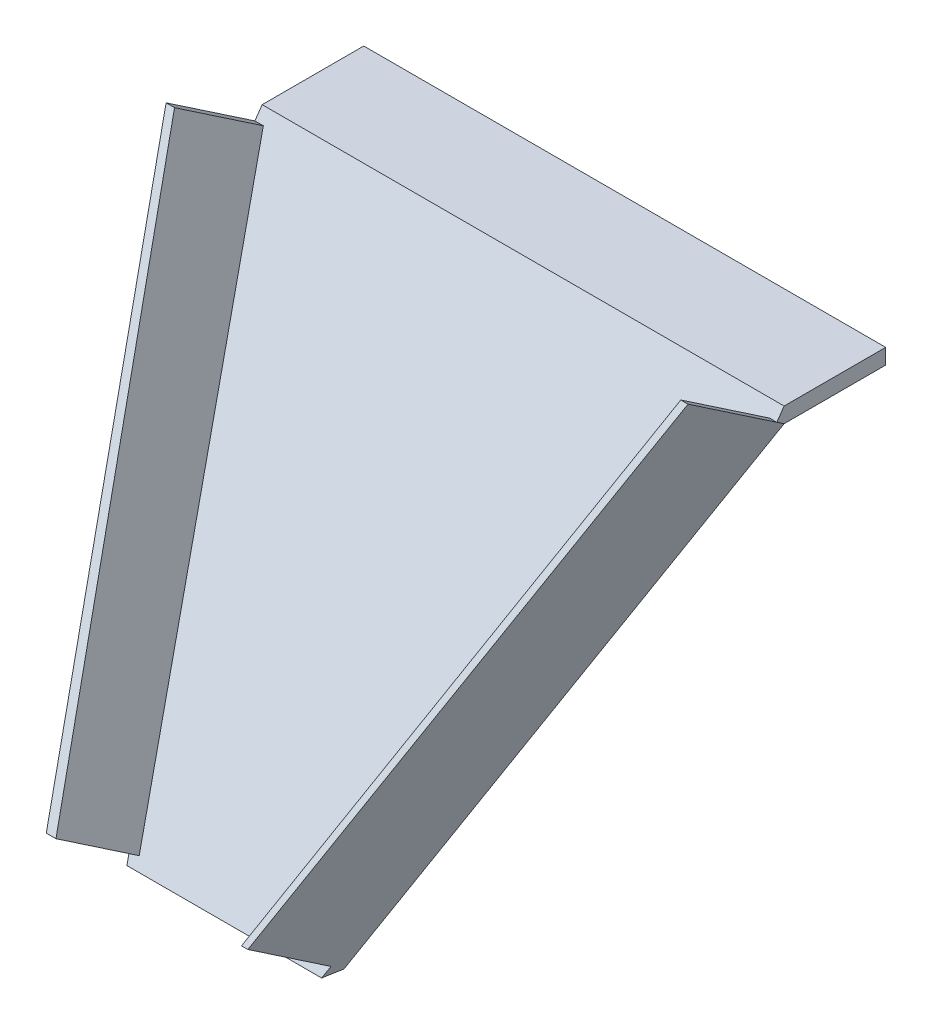
SolidWorks part; units mm, degrees
ref_plane "Front Plane" through (0, 0, 0) normal (0, 0, 1) x (1, 0, 0)
ref_plane "Top Plane" through (0, 0, 0) normal (0, 1, 0) x (1, 0, 0)
ref_plane "Right Plane" through (0, 0, 0) normal (1, 0, 0) x (0, 0, -1)
sketch "Sketch1" plane through (0, 0, 0) normal (1, 0, 0) x (0, 0, -1)
  line L0 (-25.7143, -36.9293) -> (25.7143, 36.9293)
  line L1 (25.7143, 36.9293) -> (43.2325, 36.9293)
  line L2 (43.2325, 36.9293) -> (43.2325, 34.282)
  line L3 (43.2325, 34.282) -> (25.7143, 34.282)
  line L4 (25.7143, 34.282) -> (-22.4606, -36.9293)
  line L5 (-22.4606, -36.9293) -> (-25.7143, -36.9293)
  point P4 (0, 0)
  point P5 (0, 0)
  point P7 (16.8772, 41.7152)
extrude "Boss-Extrude1" add sketch "Sketch1" along normal blind 90
sketch "Sketch5" plane through (0, -1.1706, -1.7304) normal (0, -0.5603, -0.8283) x (-1, 0, 0)
  line L0 (-90, 42.8032) -> (-61.6829, -44.9959)
  line L1 (-90, -44.9959) -> (0, -44.9959) construction
extrude "Cut-Extrude-Thin5" cut sketch "Sketch5" against normal blind 90 and the other way through all thin
sketch "Sketch6" plane through (0, -1.1706, -1.7304) normal (0, -0.5603, -0.8283) x (-1, 0, 0)
  line L0 (0, 42.8032) -> (-28.1023, -44.9959)
  line L1 (-61.6829, -44.9959) -> (0, -44.9959) construction
extrude "Cut-Extrude-Thin6" cut sketch "Sketch6" against normal blind 90 and the other way through all thin thin type one direction reverse wall 30
sketch "Sketch7" plane through (0, -1.1706, -1.7304) normal (0, -0.5603, -0.8283) x (-1, 0, 0)
  line L0 (-88.7527, 42.8032) -> (-61.1775, -43.1728)
  line L1 (-90, 42.8032) -> (0, 42.8032) construction
  line L2 (-62.2709, -43.1728) -> (-27.5188, -43.1728) construction
  line L7 (-27.5188, -43.1728) -> (0, 42.8032)
  line L8 (0, 42.8032) -> (-90, 42.8032)
  line L9 (-90, 42.8032) -> (-62.2709, -43.1728)
  line L10 (-62.2709, -43.1728) -> (-27.5188, -43.1728)
  line L12 (-88.7527, 42.8032) -> (-90, 42.8032)
  line L13 (-90, 42.8032) -> (-62.2709, -43.1728)
  line L14 (-62.2709, -43.1728) -> (-61.1775, -43.1728)
  dimension "D1" = 0
extrude "Boss-Extrude2" add sketch "Sketch7" against normal blind 20
sketch "Sketch8" plane through (0, -1.1706, -1.7304) normal (0, -0.5603, -0.8283) x (-1, 0, 0)
  line L0 (-1.4559, 42.8032) -> (-29.1844, -43.1728)
  line L1 (-90, 42.8032) -> (0, 42.8032) construction
  line L2 (-62.2709, -43.1728) -> (-27.5188, -43.1728) construction
  line L7 (-90, 42.8032) -> (-62.2709, -43.1728)
  line L8 (-62.2709, -43.1728) -> (-27.5188, -43.1728)
  line L9 (-27.5188, -43.1728) -> (0, 42.8032)
  line L10 (0, 42.8032) -> (-90, 42.8032)
  line L12 (-62.2709, -43.1728) -> (-29.1844, -43.1728)
  line L14 (-1.4559, 42.8032) -> (-90, 42.8032)
  line L15 (-90, 42.8032) -> (-62.2709, -43.1728)
  line M6 (-62.2709, -43.1728) -> (-27.5188, -43.1728)
  line M7 (-27.5188, -43.1728) -> (0, 42.8032)
  line M8 (0, 42.8032) -> (-90, 42.8032)
  dimension "D1" = 0
extrude "Boss-Extrude3" add sketch "Sketch8" against normal blind 20 contours L0 M8 M6 M7
